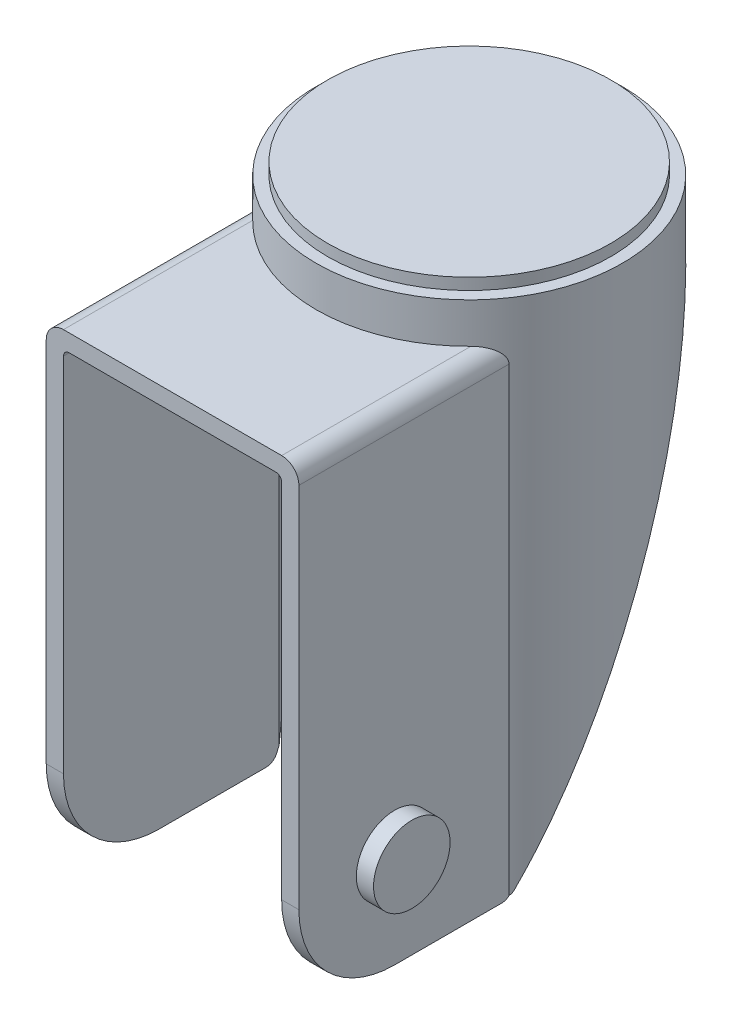
SolidWorks part; units mm, degrees
ref_plane "前视基准面" through (0, 0, 0) normal (0, 0, 1) x (1, 0, 0)
ref_plane "上视基准面" through (0, 0, 0) normal (0, 1, 0) x (1, 0, 0)
ref_plane "右视基准面" through (0, 0, 0) normal (1, 0, 0) x (0, 0, -1)
ref_plane "基准面4" through (0, 0, 0) normal (0, 0, 1) x (1, 0, 0)
sketch "草图1" plane through (0, 0, 0) normal (0, 0, 1) x (1, 0, 0)
  line L0 (0, -18) -> (24.6667, -18)
  line L1 (24.6667, -18) -> (24.6667, -20)
  line L2 (24.6667, -20) -> (26.6667, -20)
  line L3 (26.6667, -20) -> (26.6667, -162)
  line L4 (26.6667, -162) -> (0, -162)
  line L5 (0, -162) -> (0, -18)
  line L6 (0, -162) -> (0, -18) construction
revolve "旋转1" add sketch "草图1" angle 360 about L6
ref_plane "基准面5" through (0, 0, 0) normal (0, 0, 1) x (1, 0, 0)
sketch "草图2" plane through (0, 0, 0) normal (0, 0, 1) x (1, 0, 0)
  line L0 (-22, -171) -> (-19, -171)
  line L1 (-19, -171) -> (-19, -31)
  line L2 (-18, -30) -> (18, -30)
  line L3 (19, -31) -> (19, -171)
  line L4 (19, -171) -> (22, -171)
  line L5 (22, -171) -> (22, -30)
  line L6 (19, -27) -> (-19, -27)
  line L7 (-22, -30) -> (-22, -171)
  arc A0 (-19, -31) -> (-18, -30) centre (-18, -31) cw
  arc A1 (18, -30) -> (19, -31) centre (18, -31) cw
  arc A2 (22, -30) -> (19, -27) centre (19, -30) ccw
  arc A3 (-19, -27) -> (-22, -30) centre (-19, -30) ccw
extrude "凸台-拉伸1" add sketch "草图2" along normal blind 96
ref_plane "基准面6" through (0, 0, 0) normal (0, 0, 1) x (1, 0, 0)
sketch "草图3" plane through (0, 0, 0) normal (0, 0, 1) x (1, 0, 0)
  line L0 (-19, -171) -> (19, -171)
  line L1 (19, -171) -> (19, -31)
  line L2 (18, -30) -> (-18, -30)
  line L3 (-19, -31) -> (-19, -171)
  arc A0 (19, -31) -> (18, -30) centre (18, -31) ccw
  arc A1 (-18, -30) -> (-19, -31) centre (-18, -31) ccw
extrude "切除-拉伸1" cut sketch "草图3" along normal blind 96
ref_plane "基准面7" through (0, -21, 0) normal (0, 1, 0) x (1, 0, 0)
sketch "草图4" plane through (0, -21, 0) normal (0, 1, 0) x (1, 0, 0)
  circle A0 centre (0, 0) radius 23.6667
extrude "切除-拉伸2" cut sketch "草图4" against normal blind 144
ref_plane "基准面8" through (0, 0, 0) normal (1, 0, 0) x (0, 0, -1)
sketch "草图5" plane through (0, 0, 0) normal (1, 0, 0) x (0, 0, -1)
  line L0 (-150, -250) -> (50, -250)
  line L1 (50, -250) -> (50, -27)
  line L2 (50, -27) -> (25.5851, -27)
  line L3 (20.0913, -30.5878) -> (-14.5451, -109.4707)
  line L4 (-16.3763, -110.6667) -> (-35, -110.6667)
  line L5 (-51.6667, -94) -> (-51.6667, 0)
  line L6 (-51.6667, 0) -> (-150, 0)
  line L7 (-150, 0) -> (-150, -250)
  arc A0 (25.5851, -27) -> (20.0913, -30.5878) centre (25.5851, -33) ccw
  arc A1 (-14.5451, -109.4707) -> (-16.3763, -110.6667) centre (-16.3763, -108.6667) cw
  arc A2 (-35, -110.6667) -> (-51.6667, -94) centre (-35, -94) cw
extrude "切除-拉伸3" cut sketch "草图5" against normal blind 96 and the other way blind 96
ref_plane "基准面9" through (0, 0, 35) normal (0, 0, 1) x (1, 0, 0)
sketch "草图6" plane through (0, 0, 35) normal (0, 0, 1) x (1, 0, 0)
  line L0 (-34, -94) -> (-34, -90.6026)
  line L1 (-34, -90.6026) -> (-33.2308, -89.8333)
  line L2 (-33.2308, -89.8333) -> (-30, -89.8333)
  line L3 (-28.5, -85.6667) -> (-22, -85.6667)
  line L4 (-22, -85.6667) -> (-22, -94)
  line L5 (-22, -94) -> (-34, -94)
  line L6 (-22, -94) -> (-30, -94) construction
  arc A0 (-30, -89.8333) -> (-28.5, -85.6667) centre (-22.3187, -90.2453) cw
revolve "旋转2" add sketch "草图6" angle 360 about L6
ref_plane "基准面10" through (-22, 0, 0) normal (1, 0, 0) x (0, 0, -1)
sketch "草图7" plane through (-22, 0, 0) normal (1, 0, 0) x (0, 0, -1)
  line L0 (-42.1429, -89.8761) -> (-42.1429, -98.1239)
  line L1 (-42.1429, -98.1239) -> (-35, -102.2479)
  line L2 (-35, -102.2479) -> (-27.8571, -98.1239)
  line L3 (-27.8571, -98.1239) -> (-27.8571, -89.8761)
  line L4 (-27.8571, -89.8761) -> (-35, -85.7521)
  line L5 (-35, -85.7521) -> (-42.1429, -89.8761)
  circle A0 centre (-35, -94) radius 9.1923
extrude "切除-拉伸4" cut sketch "草图7" against normal blind 20
ref_plane "基准面11" through (22, 0, 0) normal (1, 0, 0) x (0, 0, -1)
sketch "草图8" plane through (22, 0, 0) normal (1, 0, 0) x (0, 0, -1)
  circle A0 centre (-35, -94) radius 6.6667
extrude "凸台-拉伸2" add sketch "草图8" along normal blind 3
